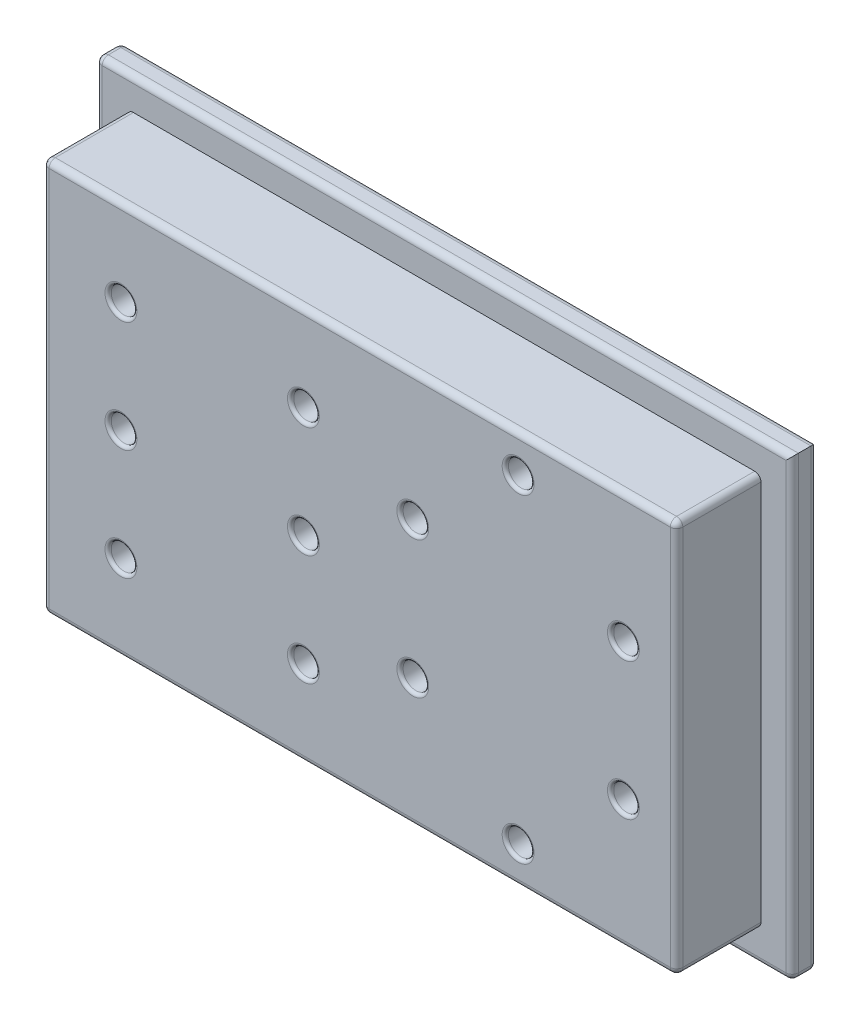
SolidWorks part; units mm, degrees
ref_plane "정면" through (0, 0, 0) normal (0, 0, 1) x (1, 0, 0)
ref_plane "윗면" through (0, 0, 0) normal (0, 1, 0) x (1, 0, 0)
ref_plane "우측면" through (0, 0, 0) normal (1, 0, 0) x (0, 0, -1)
sketch "스케치1" plane through (0, 0, 0) normal (0, 0, 1) x (1, 0, 0)
  line L1 (-50.7, 31.5) -> (50.7, 31.5)
  line L2 (-50.7, 31.5) -> (-50.7, -31.5)
  line L3 (-50.7, -31.5) -> (50.7, -31.5)
  line L4 (50.7, 31.5) -> (50.7, -31.5)
  point P4 (0, 31.5)
  point P6 (50.7, 0)
  dimension "D1" = 101.4
  dimension "D2" = 63
extrude "보스-돌출1" add sketch "스케치1" along normal blind 13.5
sketch "스케치2" plane through (0, 0, 13.5) normal (0, 0, 1) x (1, 0, 0)
  line L0 (-38.2, 17.75) -> (-9, 17.75) construction
  line L1 (-9, 17.75) -> (-9, -17.75) construction
  line L2 (-9, -17.75) -> (-38.2, -17.75) construction
  line L3 (-38.2, -17.75) -> (-38.2, 17.75) construction
  line L4 (8.5, -10.95) -> (42.2, -10.95) construction
  line L5 (42.2, -10.95) -> (42.2, 10.95) construction
  line L6 (42.2, 10.95) -> (8.5, 10.95) construction
  line L7 (8.5, 10.95) -> (8.5, -10.95) construction
  line L8 (8.5, 0) -> (42.2, 0) construction
  line L9 (25.35, 25.55) -> (25.35, -25.55) construction
  line L10 (-50.7, 31.5) -> (-50.7, -31.5) construction
  line L11 (50.7, -31.5) -> (50.7, 31.5) construction
  circle A0 centre (-38.2, 17.75) radius 2.05
  circle A1 centre (-38.2, 0) radius 2.05
  circle A2 centre (-38.2, -17.75) radius 2.05
  circle A3 centre (-9, 17.75) radius 2.05
  circle A4 centre (-9, 0) radius 2.05
  circle A5 centre (-9, -17.75) radius 2.05
  circle A6 centre (25.35, 25.55) radius 2.05
  circle A7 centre (8.5, 10.95) radius 2.05
  circle A8 centre (8.5, -10.95) radius 2.05
  circle A9 centre (42.2, 10.95) radius 2.05
  circle A10 centre (42.2, -10.95) radius 2.05
  circle A11 centre (25.35, -25.55) radius 2.05
  point P25 (-38.2, 0)
  point P27 (-9, 0)
  point P28 (25.35, 0)
  dimension "D1" = 4.1
  dimension "D2" = 35.5
  dimension "D3" = 29.2
  dimension "D4" = 12.5
  dimension "D5" = 33.7
  dimension "D6" = 21.9
  dimension "D7" = 51.1
  dimension "D8" = 8.5
sketch "스케치3" plane through (0, 0, 0) normal (0, 0, -1) x (-1, 0, 0)
  line L0 (-50.7, 31.5) -> (50.7, 31.5) construction
  line L1 (-55.7, 36.5) -> (55.7, 36.5)
  line L2 (-55.7, 36.5) -> (-55.7, -36.5)
  line L3 (-55.7, -36.5) -> (55.7, -36.5)
  line L4 (55.7, 36.5) -> (55.7, -36.5)
  line L5 (-50.7, -31.5) -> (-50.7, 31.5) construction
  point P4 (0, 36.5)
  point P6 (55.7, 0)
  dimension "D1" = 5
  dimension "D2" = 5
extrude "보스-돌출2" add sketch "스케치3" along normal blind 4
fillet "필렛1" radius 1 19 edges at (-50.7, 31.5, 6.75) (50.7, 31.5, 6.75) (50.7, -31.5, 6.75) (-50.7, -31.5, 6.75) (0, -31.5, 13.5) (-50.7, 0, 13.5) (50.7, 0, 13.5) (0, 31.5, 13.5) (0, 36.5, -4) (-55.7, 0, -4) (0, -36.5, -4) (55.7, 0, -4) (-55.7, 0, 0) (0, 36.5, 0) (55.7, 0, 0) (0, -36.5, 0) (55.7, -36.5, -2) (-55.7, -36.5, -2) (-55.7, 36.5, -2)
extrude "컷-돌출1" cut sketch "스케치2" against normal through all
fillet "필렛2" radius 0.5 24 edges at (-36.15, 17.75, 13.5) (27.4, 25.55, 13.5) (10.55, 10.95, 13.5) (10.55, -10.95, 13.5) (44.25, 10.95, 13.5) (44.25, -10.95, 13.5) (27.4, -25.55, 13.5) (-6.95, -17.75, 13.5) (-6.95, 0, 13.5) (-6.95, 17.75, 13.5) (-36.15, -17.75, 13.5) (-36.15, 0, 13.5) (-36.15, 17.75, -4) (27.4, 25.55, -4) (10.55, 10.95, -4) (10.55, -10.95, -4) (44.25, 10.95, -4) (44.25, -10.95, -4) (27.4, -25.55, -4) (-6.95, -17.75, -4) (-6.95, 0, -4) (-6.95, 17.75, -4) (-36.15, -17.75, -4) (-36.15, 0, -4)
sketch "스케치4" plane through (0, 0, -4) normal (0, 0, -1) x (-1, 0, 0)
  line L0 (43.7, 24.5) -> (43.7, -24.5) construction
  line L1 (43.7, -24.5) -> (-43.7, -24.5) construction
  line L2 (-43.7, -24.5) -> (-43.7, 24.5) construction
  line L3 (-43.7, 24.5) -> (43.7, 24.5) construction
  line L4 (55.7, 35.5) -> (55.7, -35.5) construction
  line L5 (-55.7, 36.5) -> (54.7, 36.5) construction
  circle A0 centre (-43.7, 24.5) radius 4.75
  circle A1 centre (-43.7, -24.5) radius 4.75
  circle A2 centre (43.7, -24.5) radius 4.75
  circle A3 centre (43.7, 24.5) radius 4.75
  point P8 (0, 24.5)
  point P9 (-43.7, 0)
  dimension "D1" = 9.5
  dimension "D2" = 12
  dimension "D3" = 12
extrude "컷-돌출2" cut sketch "스케치4" against normal blind 5
fillet "필렛3" radius 0.5 4 edges at (38.95, -24.5, -4) (-48.45, -24.5, -4) (-48.45, 24.5, -4) (38.95, 24.5, -4)
